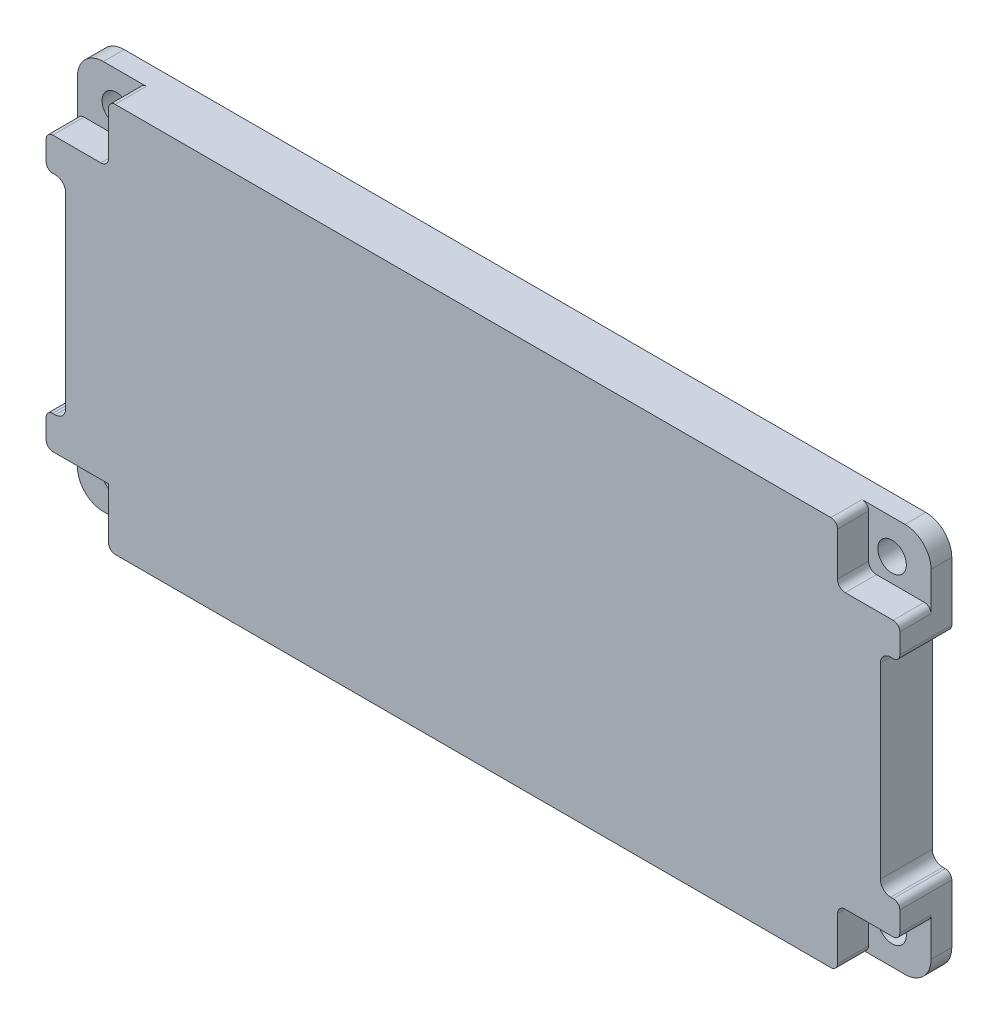
SolidWorks part; units mm, degrees
ref_plane "정면" through (0, 0, 0) normal (0, 0, 1) x (1, 0, 0)
ref_plane "윗면" through (0, 0, 0) normal (0, 1, 0) x (1, 0, 0)
ref_plane "우측면" through (0, 0, 0) normal (1, 0, 0) x (0, 0, -1)
sketch "스케치2" plane through (0, 0, 0) normal (0, 0, 1) x (1, 0, 0)
  line L0 (32.85, 15) -> (-32.85, -15) construction
  line L1 (-32.85, -15) -> (-32.85, 15)
  line L2 (-32.85, -15) -> (32.85, -15)
  line L3 (32.85, -15) -> (32.85, 15)
  line L4 (-32.85, 15) -> (32.85, 15)
  line L5 (32.85, -15) -> (-32.85, 15) construction
  point P0 (0, 0)
  dimension "D1" = 30
  dimension "D2" = 65.7
  dimension "D3" = 30
  dimension "D4" = 65.7
extrude "보스-돌출1" add sketch "스케치2" along normal blind 4
fillet "필렛1" radius 2 4 edges at (-32.85, -15, 2) (32.85, -15, 2) (-32.85, 15, 2) (32.85, 15, 2)
ref_plane "평면1" through (0, 0, 4) normal (0, 0, 1) x (1, 0, 0)
sketch "스케치3" plane through (0, 0, 4) normal (0, 0, 1) x (1, 0, 0)
  line L0 (-32.85, 0) -> (32.85, 0) construction
  line L1 (-28.05, 10.55) -> (-32.85, 10.55)
  line L2 (-28.05, 10.55) -> (-28.05, 15)
  line L3 (-28.05, 15) -> (-32.85, 15)
  line L4 (-32.85, 10.55) -> (-32.85, 15)
  line L5 (32.85, -13) -> (32.85, 13) construction
  line L6 (30.85, 15) -> (-30.85, 15) construction
  line L7 (-32.85, 13) -> (-32.85, -13) construction
  line L8 (-32.85, -10.55) -> (-32.85, -15)
  line L9 (-28.05, -15) -> (-32.85, -15)
  line L10 (-28.05, -10.55) -> (-28.05, -15)
  line L11 (-28.05, -10.55) -> (-32.85, -10.55)
  line L12 (0, 15) -> (0, -15) construction
  line L13 (-30.85, -15) -> (30.85, -15) construction
  line L14 (28.05, -10.55) -> (32.85, -10.55)
  line L15 (28.05, -10.55) -> (28.05, -15)
  line L16 (28.05, -15) -> (32.85, -15)
  line L17 (32.85, -10.55) -> (32.85, -15)
  line L18 (32.85, 10.55) -> (32.85, 15)
  line L19 (28.05, 15) -> (32.85, 15)
  line L20 (28.05, 10.55) -> (28.05, 15)
  line L21 (28.05, 10.55) -> (32.85, 10.55)
  circle A0 centre (-29.85, 12.35) radius 1.1
  circle A1 centre (-29.85, -12.35) radius 1.1
  circle A2 centre (29.85, -12.35) radius 1.1
  circle A3 centre (29.85, 12.35) radius 1.1
  point P8 (-29.85, 12.35)
  dimension "D1" = 4.8
  dimension "D2" = 4.45
  dimension "D3" = 1.8
  dimension "D4" = 1.8
ref_plane "평면2" through (0, 0, 4) normal (0, 0, 1) x (1, 0, 0)
sketch "스케치5" plane through (0, 0, 4) normal (0, 0, 1) x (1, 0, 0)
  line L1 (30.85, 15) -> (-30.85, 15) construction
  line L2 (-30.85, -15) -> (30.85, -15) construction
  line L3 (0, 15) -> (0, -15) construction
  line L4 (30.85, 15) -> (-30.85, 15) construction
  line L7 (-32.85, 8) -> (-31.35, 8)
  line L8 (-32.85, 8) -> (-32.85, -8)
  line L9 (-32.85, -8) -> (-31.35, -8)
  line L10 (-31.35, 8) -> (-31.35, -8)
  line L11 (-32.85, 13) -> (-32.85, -13) construction
  line L12 (31.35, 8) -> (31.35, -8)
  line L13 (32.85, -8) -> (31.35, -8)
  line L14 (32.85, 8) -> (32.85, -8)
  line L15 (32.85, 8) -> (31.35, 8)
  line L16 (-32.85, 0) -> (32.85, 0) construction
  circle A0 centre (-29.85, 12.35) radius 1.1
  circle A1 centre (29.85, 12.35) radius 1.1
  circle A2 centre (29.85, -12.35) radius 1.1
  circle A3 centre (-29.85, -12.35) radius 1.1
  dimension "D1" = 7
  dimension "D2" = 7
extrude "컷-돌출6" cut sketch "스케치5" against normal through all
extrude "컷-돌출5" cut sketch "스케치3" against normal blind 2.4
fillet "필렛7" radius 0.51 8 edges at (-28.05, -15, 2.8) (-32.85, -10.55, 2.8) (28.05, -15, 2.8) (32.85, -10.55, 2.8) (32.85, 10.55, 2.8) (28.05, 15, 2.8) (-28.05, 15, 2.8) (-32.85, 10.55, 2.8)
fillet "필렛8" radius 0.6 3 edges at (28.05, -10.55, 2.8) (28.05, 10.55, 2.8) (-28.05, 10.55, 2.8)
fillet "필렛9" radius 0.5 4 edges at (-32.85, 8, 2) (-32.85, -8, 2) (32.85, -8, 2) (32.85, 8, 2)
fillet "필렛10" radius 0.8 4 edges at (31.35, 8, 2) (31.35, -8, 2) (-31.35, -8, 2) (-31.35, 8, 2)
ref_plane "평면3" through (0, 0, 4) normal (0, 0, 1) x (1, 0, 0)
sketch "스케치6" plane through (0, 0, 4) normal (0, 0, 1) x (1, 0, 0)
  line L0 (-32.85, 10.04) -> (-32.85, 8.5) construction
  circle A0 centre (-17.85, 0) radius 4.55
  point P0 (-17.85, 0)
  point P1 (-32.85, 9.27)
  dimension "D2" = 9.1
  dimension "D1" = 15
